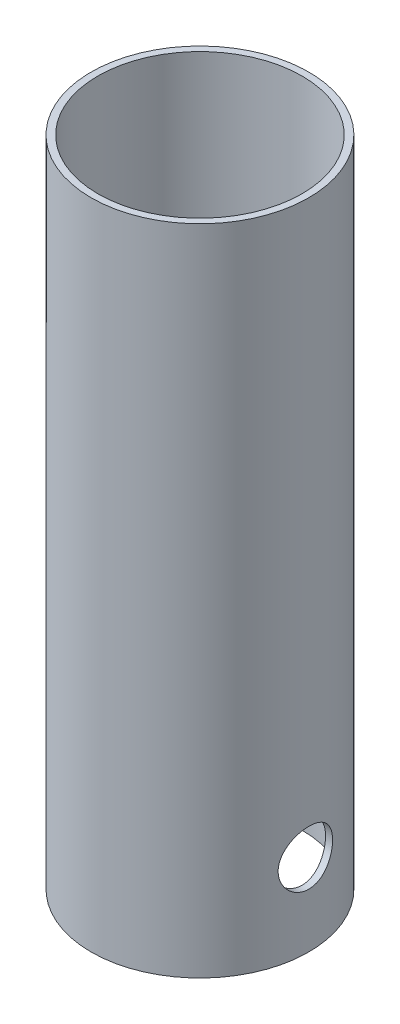
SolidWorks part; units mm, degrees
ref_plane "Front Plane" through (0, 0, 0) normal (0, 0, 1) x (1, 0, 0)
ref_plane "Top Plane" through (0, 0, 0) normal (0, 1, 0) x (1, 0, 0)
ref_plane "Right Plane" through (0, 0, 0) normal (1, 0, 0) x (0, 0, -1)
sketch "Sketch1" plane through (0, 0, 0) normal (0, 1, 0) x (1, 0, 0)
  circle A0 centre (0, 0) radius 47.625
  circle A1 centre (0, 0) radius 50.8
  dimension "D1" = 3.175
  dimension "D2" = 101.6
extrude "Boss-Extrude1" add sketch "Sketch1" along normal blind 304.8
sketch "Sketch2" plane through (0, 0, 0) normal (1, 0, 0) x (0, 0, -1)
  line L0 (0, 304.8) -> (0, 0) construction
  line L1 (-50.8, 0) -> (50.8, 0) construction
  circle A0 centre (0, 38.1) radius 12.7
  dimension "D2" = 25.4
  dimension "D1" = 38.1
extrude "Cut-Extrude1" cut sketch "Sketch2" along normal through all
